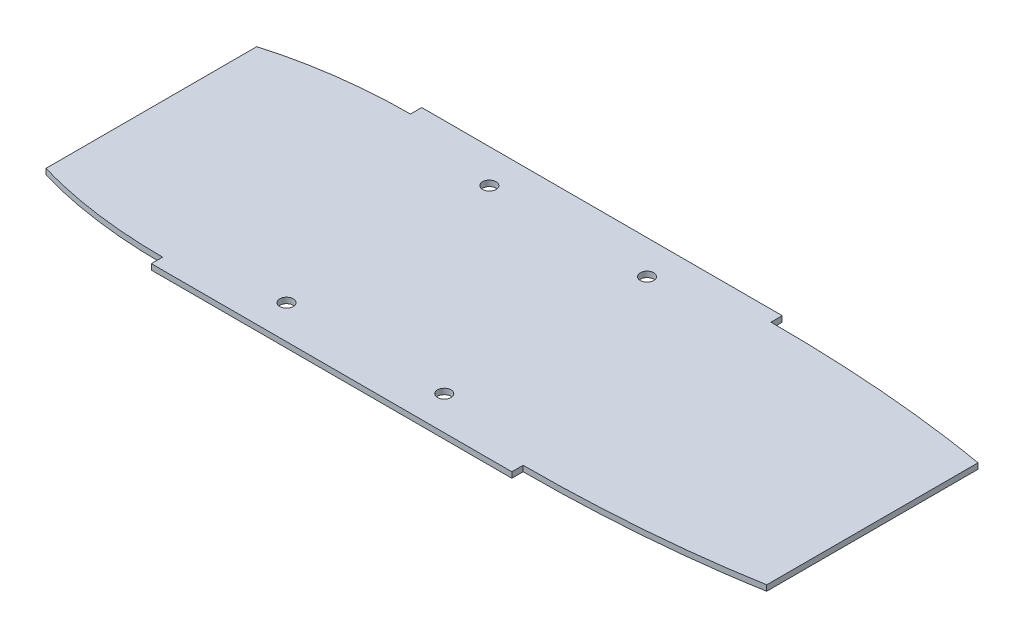
SolidWorks part; units mm, degrees
ref_plane "Front Plane" through (0, 0, 0) normal (0, 0, 1) x (1, 0, 0)
ref_plane "Top Plane" through (0, 0, 0) normal (0, 1, 0) x (1, 0, 0)
ref_plane "Right Plane" through (0, 0, 0) normal (1, 0, 0) x (0, 0, -1)
sketch "Sketch1" plane through (0, 0, 0) normal (0, 1, 0) x (1, 0, 0)
  line L1 (76.2, 38.1) -> (177.8, 38.1)
  line L3 (76.2, -38.1) -> (177.8, -38.1)
  ellipse E0 centre (76.2, 0) end of major axis (0, 0) minor radius 38.1 (76.2, 38.1) -> (76.2, -38.1) ccw
  ellipse E1 centre (177.8, 0) end of major axis (304.8, 0) minor radius 38.1 (177.8, -38.1) -> (177.8, 38.1) ccw
  point P0 (0, 0)
  dimension "D1" = 101.6
  dimension "D2" = 76.2
  dimension "D3" = 127
  dimension "D4" = 76.2
extrude "Boss-Extrude1" add sketch "Sketch1" along normal blind 25.4
sketch "Sketch2" plane through (0, 0, 0) normal (1, 0, 0) x (0, 0, -1)
  line L2 (-38.1, 25.4) -> (-38.1, 0) construction
  line L3 (-38.1, 0) -> (38.1, 0) construction
  circle A0 centre (0, 93.3971) radius 57.15
  point P5 (-38.1, 50.8)
  dimension "D1" = 114.3
  dimension "D2" = 50.8
extrude "Cut-Extrude2" [suppressed] cut sketch "Sketch2" along normal through all
sketch "Sketch3" plane through (0, 0, 0) normal (0, -1, 0) x (1, 0, 0)
  line L1 (152.4, -61.0376) -> (-25.885, -61.0376)
  line L2 (152.4, -61.0376) -> (152.4, 51.2506)
  line L3 (152.4, 51.2506) -> (-25.885, 51.2506)
  line L4 (-25.885, -61.0376) -> (-25.885, 51.2506)
  line L5 (152.4, -61.0376) -> (-25.885, 51.2506) construction
  line L6 (152.4, 51.2506) -> (-25.885, -61.0376) construction
  point P0 (63.2575, -4.8935)
  dimension "D1" = 152.4
extrude "Cut-Extrude3" [suppressed] cut sketch "Sketch3" against normal through all
sketch "Sketch4" plane through (0, 0, 0) normal (0, -1, 0) x (1, 0, 0)
  line L0 (177.8, -38.1) -> (76.2, -38.1) construction
  line L1 (139.7, -38.1) -> (76.2, -38.1)
  line L2 (139.7, -38.1) -> (139.7, 38.1)
  line L3 (139.7, 38.1) -> (76.2, 38.1)
  line L4 (76.2, -38.1) -> (76.2, 38.1)
  line L5 (139.7, -38.1) -> (76.2, 38.1) construction
  line L6 (139.7, 38.1) -> (76.2, -38.1) construction
  point P0 (107.95, 0)
  dimension "D1" = 63.5
extrude "Cut-Extrude4" cut sketch "Sketch4" against normal blind 0.01
hole_wizard "#6 Clearance Hole1" positions "Sketch5" profile "Sketch6" hole size "#6" standard "ANSI Inch" end condition through all
sketch "Sketch5" plane through (0, 25.4, 0) normal (0, 1, 0) x (1, 0, 0)
  line L0 (104.775, 28.575) -> (104.775, -28.575) construction
  line L3 (76.2, -38.1) -> (177.8, -38.1) construction
  point P0 (104.775, 28.575)
  point P2 (149.225, 28.575)
  point P4 (149.225, -28.575)
  point P6 (104.775, -28.575)
  dimension "D1" = 44.45
  dimension "D2" = 57.15
  dimension "D3" = 28.575
  dimension "D4" = 9.525
sketch "Sketch6" plane through (104.775, 25.4, -28.575) normal (1, 0, 0) x (0, 0, 1)
  line L0 (0, 0) -> (0, 25.4)
  line L1 (0, 25.4) -> (1.8986, 25.4)
  line L2 (1.8986, 25.4) -> (1.8986, 0)
  line L5 (1.8986, 0) -> (0, 0)
  line L11 (0, -6.35) -> (0, 107.95) construction
  dimension "Thru Hole Dia." = 3.7973
  dimension "Thru Hole Depth" = 25.4
sketch "Sketch7" plane through (0, 25.4, 0) normal (0, 1, 0) x (1, 0, 0)
  line L1 (144.0924, 28.575) -> (146.6587, 24.13)
  line L2 (146.6587, 24.13) -> (151.7913, 24.13)
  line L3 (151.7913, 24.13) -> (154.3576, 28.575)
  line L4 (154.3576, 28.575) -> (151.7913, 33.02)
  line L5 (151.7913, 33.02) -> (146.6587, 33.02)
  line L6 (146.6587, 33.02) -> (144.0924, 28.575)
  line L7 (144.0924, -28.575) -> (146.6587, -33.02)
  line L8 (146.6587, -33.02) -> (151.7913, -33.02)
  line L9 (151.7913, -33.02) -> (154.3576, -28.575)
  line L10 (154.3576, -28.575) -> (151.7913, -24.13)
  line L11 (151.7913, -24.13) -> (146.6587, -24.13)
  line L12 (146.6587, -24.13) -> (144.0924, -28.575)
  line L13 (99.6424, -28.575) -> (102.2087, -33.02)
  line L14 (102.2087, -33.02) -> (107.3413, -33.02)
  line L15 (107.3413, -33.02) -> (109.9076, -28.575)
  line L16 (109.9076, -28.575) -> (107.3413, -24.13)
  line L17 (107.3413, -24.13) -> (102.2087, -24.13)
  line L18 (102.2087, -24.13) -> (99.6424, -28.575)
  line L19 (99.6424, 28.575) -> (102.2087, 24.13)
  line L20 (102.2087, 24.13) -> (107.3413, 24.13)
  line L21 (107.3413, 24.13) -> (109.9076, 28.575)
  line L22 (109.9076, 28.575) -> (107.3413, 33.02)
  line L23 (107.3413, 33.02) -> (102.2087, 33.02)
  line L24 (102.2087, 33.02) -> (99.6424, 28.575)
  circle A0 centre (149.225, 28.575) radius 4.445 construction
  circle A1 centre (149.225, -28.575) radius 4.445 construction
  circle A2 centre (104.775, -28.575) radius 4.445 construction
  circle A3 centre (104.775, 28.575) radius 4.445 construction
  dimension "D1" = 8.89
  dimension "D2" = 8.89
  dimension "D3" = 8.89
  dimension "D4" = 8.89
extrude "Cut-Extrude5" cut sketch "Sketch7" against normal blind 3.5052
sketch "Sketch8" plane through (0, 25.4, 0) normal (0, 1, 0) x (1, 0, 0)
  line L4 (177.8, 34.925) -> (76.2, 34.925)
  line L5 (76.2, -34.925) -> (177.8, -34.925)
  line L54 (76.2, 34.925) -> (76.2, 38.1)
  line L56 (177.8, 38.1) -> (76.2, 38.1) construction
  line L57 (177.8, 38.1) -> (177.8, 34.925)
  line L58 (76.2, -34.925) -> (76.2, -38.1)
  line L59 (76.2, -38.1) -> (177.8, -38.1)
  line L60 (177.8, -38.1) -> (177.8, -34.925)
  line L61 (76.2, 38.1) -> (177.8, 38.1)
  circle A0 centre (149.225, 28.575) radius 1.8987 construction
  circle A1 centre (149.225, -28.575) radius 1.8987 construction
  circle A2 centre (104.775, -28.575) radius 1.8986 construction
  circle A3 centre (104.775, 28.575) radius 1.8986 construction
  circle A4 centre (149.225, 28.575) radius 1.8987
  circle A5 centre (149.225, -28.575) radius 1.8987
  circle A6 centre (104.775, -28.575) radius 1.8986
  circle A7 centre (104.775, 28.575) radius 1.8986
  ellipse E2 centre (177.8, 0) end of major axis (50.8, 0) minor radius 38.1 (177.8, -38.1) -> (177.8, 38.1) ccw construction
  spline S0 degree 3 poles (-1377.8045, 1206.3591) (-854.0921, 797.9266) (-294.8884, -54.3183) (200.1699, -34.3631) (205.7465, -34.0245) (216.8803, -33.103) (222.4374, -32.5204) (230.7563, -31.4365) (233.5264, -31.04) (239.0605, -30.1693) (241.8261, -29.6947) (250.0889, -28.1436) (255.5586, -26.9423) (262.3286, -25.1517) (263.6791, -24.7789) (266.3727, -24.0005) (267.7168, -23.5946) (271.7259, -22.3246) (274.3674, -21.4094) (279.5692, -19.3996) (282.1298, -18.3061) (285.883, -16.4724) (287.1192, -15.8286) (289.5537, -14.4572) (290.7521, -13.7299) (293.0968, -12.1607) (294.2462, -11.3161) (295.8747, -9.9512) (296.4028, -9.4789) (297.4219, -8.4911) (297.9134, -7.9747) (298.8341, -6.9028) (299.2652, -6.3459) (300.0511, -5.1769) (300.4066, -4.5643) (301.0089, -3.2659) (301.247, -2.5978) (301.485, -1.5601) (301.5446, -1.2061) (301.6178, -0.4946) (301.6449, 0.2142) (301.5814, 0.9176) (301.4741, 1.6184) (301.3978, 1.9698) (301.1113, 3.0015) (300.8464, 3.657) (300.2067, 4.9201) (299.8287, 5.531) (299.0071, 6.6864) (298.5626, 7.2341) (297.6228, 8.2846) (297.1274, 8.7872) (296.0961, 9.7565) (295.5585, 10.2242) (293.9164, 11.5662) (292.7775, 12.3858) (290.4399, 13.9238) (289.2408, 14.6414) (286.7973, 15.9997) (285.5527, 16.6401) (283.0272, 17.8594) (281.7447, 18.4387) (279.1562, 19.5434) (277.8549, 20.0667) (273.9338, 21.5646) (271.2968, 22.4679) (265.9889, 24.1333) (263.3179, 24.8949) (255.2638, 27.0095) (249.8403, 28.1946) (238.9146, 30.2368) (233.4119, 31.0923) (225.1088, 32.1714) (222.3337, 32.4966) (216.7836, 33.0815) (214.0067, 33.3415) (205.6704, 34.0295) (200.1056, 34.3664) (-342.7454, 56.1817) (-942.1991, -973.5849) (-1486.6218, -1072.784) knots -5.414346 -5.414346 -5.414346 -5.414346 0.0625 0.0625 0.125 0.125 0.1875 0.1875 0.21875 0.21875 0.25 0.25 0.3125 0.3125 0.328125 0.328125 0.34375 0.34375 0.375 0.375 0.40625 0.40625 0.421875 0.421875 0.4375 0.4375 0.453125 0.453125 0.460937 0.460937 0.46875 0.46875 0.476562 0.476562 0.484375 0.484375 0.492187 0.492187 0.496094 0.496094 0.5 0.503906 0.503906 0.507812 0.507812 0.515625 0.515625 0.523437 0.523437 0.53125 0.53125 0.539062 0.539062 0.546875 0.546875 0.5625 0.5625 0.578125 0.578125 0.59375 0.59375 0.609375 0.609375 0.625 0.625 0.65625 0.65625 0.6875 0.6875 0.75 0.75 0.8125 0.8125 0.84375 0.84375 0.875 0.875 0.9375 0.9375 6.964681 6.964681 6.964681 6.964681 only from (177.8, -34.925) to (177.8, 34.925)
  spline S1 degree 3 poles (1055.6343, -1687.5294) (614.9818, -466.9883) (294.4055, 51.3664) (61.7544, 34.2641) (58.1825, 33.8682) (51.0865, 32.7961) (47.5624, 32.1204) (40.5691, 30.4484) (37.0996, 29.4531) (32.806, 27.9564) (31.9495, 27.6442) (30.2412, 26.9922) (29.3909, 26.6528) (26.8661, 25.5974) (25.2124, 24.8424) (21.9728, 23.2134) (20.3869, 22.3396) (17.2974, 20.4484) (15.7935, 19.4313) (13.6173, 17.7663) (12.9047, 17.1874) (11.5136, 15.9765) (10.8409, 15.3496) (9.5478, 14.0466) (8.9274, 13.3705) (8.0429, 12.3133) (7.7557, 11.9536) (7.1984, 11.2184) (6.9284, 10.8431) (5.638, 8.9421) (4.781, 7.3318) (4.0115, 5.1647) (3.8724, 4.7214) (3.631, 3.8285) (3.5287, 3.3798) (3.2787, 2.0267) (3.1875, 1.1156) (3.1705, -0.2656) (3.1851, -0.7307) (3.2544, -1.6536) (3.3089, -2.1107) (3.5286, -3.4697) (3.7502, -4.3591) (4.1852, -5.6706) (4.348, -6.1057) (4.7028, -6.9593) (4.8943, -7.3775) (5.5073, -8.6089) (5.9671, -9.3989) (6.9725, -10.9267) (7.5182, -11.6645) (8.6847, -13.0948) (9.2998, -13.7802) (11.2121, -15.7483) (12.5811, -16.951) (14.7395, -18.6328) (15.4767, -19.1727) (16.9829, -20.2157) (17.7538, -20.7198) (20.0907, -22.1703) (21.6832, -23.0577) (26.5435, -25.5293) (29.8928, -26.9256) (35.0379, -28.7409) (36.7735, -29.2986) (39.405, -30.0707) (40.2865, -30.3172) (42.0504, -30.7874) (42.9338, -31.0114) (47.3578, -32.0793) (50.919, -32.7671) (58.0795, -33.8562) (61.6788, -34.2572) (316.9315, -53.1148) (654.4248, 576.1538) (1055.7992, 1687.4516) knots -3.920308 -3.920308 -3.920308 -3.920308 0.0625 0.0625 0.125 0.125 0.1875 0.1875 0.25 0.25 0.265625 0.265625 0.28125 0.28125 0.3125 0.3125 0.34375 0.34375 0.375 0.375 0.390625 0.390625 0.40625 0.40625 0.421875 0.421875 0.429688 0.429688 0.4375 0.4375 0.46875 0.46875 0.476563 0.476563 0.484375 0.484375 0.5 0.5 0.507813 0.507813 0.515625 0.515625 0.53125 0.53125 0.539063 0.539063 0.546875 0.546875 0.5625 0.5625 0.578125 0.578125 0.59375 0.59375 0.625 0.625 0.640625 0.640625 0.65625 0.65625 0.6875 0.6875 0.75 0.75 0.78125 0.78125 0.796875 0.796875 0.8125 0.8125 0.875 0.875 0.9375 0.9375 5.285634 5.285634 5.285634 5.285634 only from (76.2, 34.925) to (76.2, -34.925)
  spline S2 degree 3 poles (177.8, -34.925) (183.4037, -34.925) (188.9985, -34.8134) (200.1699, -34.3631) (205.7465, -34.0245) (216.8803, -33.103) (222.4374, -32.5204) (230.7563, -31.4365) (233.5264, -31.04) (239.0605, -30.1693) (241.8261, -29.6947) (250.0889, -28.1436) (255.5586, -26.9423) (262.3286, -25.1517) (263.6791, -24.7789) (266.3727, -24.0005) (267.7168, -23.5946) (271.7259, -22.3246) (274.3674, -21.4094) (279.5692, -19.3996) (282.1298, -18.3061) (285.883, -16.4724) (287.1192, -15.8286) (289.5537, -14.4572) (290.7521, -13.7299) (293.0968, -12.1607) (294.2462, -11.3161) (295.8747, -9.9512) (296.4028, -9.4789) (297.4219, -8.4911) (297.9134, -7.9747) (298.8341, -6.9028) (299.2652, -6.3459) (300.0511, -5.1769) (300.4066, -4.5643) (301.0089, -3.2659) (301.247, -2.5978) (301.485, -1.5601) (301.5446, -1.2061) (301.6178, -0.4946) (301.6449, 0.2142) (301.5814, 0.9176) (301.4741, 1.6184) (301.3978, 1.9698) (301.1113, 3.0015) (300.8464, 3.657) (300.2067, 4.9201) (299.8287, 5.531) (299.0071, 6.6864) (298.5626, 7.2341) (297.6228, 8.2846) (297.1274, 8.7872) (296.0961, 9.7565) (295.5585, 10.2242) (293.9164, 11.5662) (292.7775, 12.3858) (290.4399, 13.9238) (289.2408, 14.6414) (286.7973, 15.9997) (285.5527, 16.6401) (283.0272, 17.8594) (281.7447, 18.4387) (279.1562, 19.5434) (277.8549, 20.0667) (273.9338, 21.5646) (271.2968, 22.4679) (265.9889, 24.1333) (263.3179, 24.8949) (255.2638, 27.0095) (249.8403, 28.1946) (238.9146, 30.2368) (233.4119, 31.0923) (225.1088, 32.1714) (222.3337, 32.4966) (216.7836, 33.0815) (214.0067, 33.3415) (205.6704, 34.0295) (200.1056, 34.3664) (188.9628, 34.8142) (183.3847, 34.925) (177.8, 34.925) knots 0 0 0 0 0.0625 0.0625 0.125 0.125 0.1875 0.1875 0.21875 0.21875 0.25 0.25 0.3125 0.3125 0.328125 0.328125 0.34375 0.34375 0.375 0.375 0.40625 0.40625 0.421875 0.421875 0.4375 0.4375 0.453125 0.453125 0.460937 0.460937 0.46875 0.46875 0.476562 0.476562 0.484375 0.484375 0.492187 0.492187 0.496094 0.496094 0.5 0.503906 0.503906 0.507812 0.507812 0.515625 0.515625 0.523437 0.523437 0.53125 0.53125 0.539062 0.539062 0.546875 0.546875 0.5625 0.5625 0.578125 0.578125 0.59375 0.59375 0.609375 0.609375 0.625 0.625 0.65625 0.65625 0.6875 0.6875 0.75 0.75 0.8125 0.8125 0.84375 0.84375 0.875 0.875 0.9375 0.9375 1 1 1 1
  spline S3 degree 3 poles (76.2, 34.925) (72.5604, 34.925) (68.9434, 34.7926) (61.7544, 34.2641) (58.1825, 33.8682) (51.0865, 32.7961) (47.5624, 32.1204) (40.5691, 30.4484) (37.0996, 29.4531) (32.806, 27.9564) (31.9495, 27.6442) (30.2412, 26.9922) (29.3909, 26.6528) (26.8661, 25.5974) (25.2124, 24.8424) (21.9728, 23.2134) (20.3869, 22.3396) (17.2974, 20.4484) (15.7935, 19.4313) (13.6173, 17.7663) (12.9047, 17.1874) (11.5136, 15.9765) (10.8409, 15.3496) (9.5478, 14.0466) (8.9274, 13.3705) (8.0429, 12.3133) (7.7557, 11.9536) (7.1984, 11.2184) (6.9284, 10.8431) (5.638, 8.9421) (4.781, 7.3318) (4.0115, 5.1647) (3.8724, 4.7214) (3.631, 3.8285) (3.5287, 3.3798) (3.2787, 2.0267) (3.1875, 1.1156) (3.1705, -0.2656) (3.1851, -0.7307) (3.2544, -1.6536) (3.3089, -2.1107) (3.5286, -3.4697) (3.7502, -4.3591) (4.1852, -5.6706) (4.348, -6.1057) (4.7028, -6.9593) (4.8943, -7.3775) (5.5073, -8.6089) (5.9671, -9.3989) (6.9725, -10.9267) (7.5182, -11.6645) (8.6847, -13.0948) (9.2998, -13.7802) (11.2121, -15.7483) (12.5811, -16.951) (14.7395, -18.6328) (15.4767, -19.1727) (16.9829, -20.2157) (17.7538, -20.7198) (20.0907, -22.1703) (21.6832, -23.0577) (26.5435, -25.5293) (29.8928, -26.9256) (35.0379, -28.7409) (36.7735, -29.2986) (39.405, -30.0707) (40.2865, -30.3172) (42.0504, -30.7874) (42.9338, -31.0114) (47.3578, -32.0793) (50.919, -32.7671) (58.0795, -33.8562) (61.6788, -34.2572) (68.9128, -34.7916) (72.5476, -34.925) (76.2, -34.925) knots 0 0 0 0 0.0625 0.0625 0.125 0.125 0.1875 0.1875 0.25 0.25 0.265625 0.265625 0.28125 0.28125 0.3125 0.3125 0.34375 0.34375 0.375 0.375 0.390625 0.390625 0.40625 0.40625 0.421875 0.421875 0.429688 0.429688 0.4375 0.4375 0.46875 0.46875 0.476563 0.476563 0.484375 0.484375 0.5 0.5 0.507813 0.507813 0.515625 0.515625 0.53125 0.53125 0.539063 0.539063 0.546875 0.546875 0.5625 0.5625 0.578125 0.578125 0.59375 0.59375 0.625 0.625 0.640625 0.640625 0.65625 0.65625 0.6875 0.6875 0.75 0.75 0.78125 0.78125 0.796875 0.796875 0.8125 0.8125 0.875 0.875 0.9375 0.9375 1 1 1 1
  dimension "D1" = 3.175
extrude "Boss-Extrude2" add sketch "Sketch8" along normal blind 1.5875
sketch "Sketch9" plane through (0, 0, 0) normal (1, 0, 0) x (0, 0, -1)
  line L0 (34.925, 25.4) -> (38.1, 25.4) construction
  line L1 (-41.2871, 25.4) -> (42.2254, 25.4)
  line L2 (-41.2871, 25.4) -> (-41.2871, -1.2646)
  line L3 (-41.2871, -1.2646) -> (42.2254, -1.2646)
  line L4 (42.2254, 25.4) -> (42.2254, -1.2646)
extrude "Cut-Extrude7" cut sketch "Sketch9" along normal through all
sketch "Sketch10" plane through (0, 25.4, 0) normal (0, -1, 0) x (1, 0, 0)
  line L0 (76.2, 34.925) -> (76.2, 38.1) construction
  line L1 (-38.1, 39.0175) -> (38.1, 39.0175)
  line L2 (-38.1, 39.0175) -> (-38.1, -39.0175)
  line L3 (-38.1, -39.0175) -> (38.1, -39.0175)
  line L4 (38.1, 39.0175) -> (38.1, -39.0175)
  line L5 (-38.1, 39.0175) -> (38.1, -39.0175) construction
  line L6 (-38.1, -39.0175) -> (38.1, 39.0175) construction
  line L7 (177.8, 38.1) -> (177.8, 34.925) construction
  line L8 (361.95, 44.8802) -> (241.3, 44.8802)
  line L9 (361.95, 44.8802) -> (361.95, -44.8805)
  line L10 (361.95, -44.8805) -> (241.3, -44.8805)
  line L11 (241.3, 44.8802) -> (241.3, -44.8805)
  line L12 (361.95, 44.8802) -> (241.3, -44.8805) construction
  line L13 (361.95, -44.8805) -> (241.3, 44.8802) construction
  spline S0 degree 3 poles (177.8, 34.925) (183.4037, 34.925) (188.9985, 34.8134) (200.1699, 34.3631) (205.7465, 34.0245) (216.8803, 33.103) (222.4374, 32.5204) (230.7563, 31.4365) (233.5264, 31.04) (239.0605, 30.1693) (241.8261, 29.6947) (250.0889, 28.1436) (255.5586, 26.9423) (262.3286, 25.1517) (263.6791, 24.7789) (266.3727, 24.0005) (267.7168, 23.5946) (271.7259, 22.3246) (274.3674, 21.4094) (279.5692, 19.3996) (282.1298, 18.3061) (285.883, 16.4724) (287.1192, 15.8286) (289.5537, 14.4572) (290.7521, 13.7299) (293.0968, 12.1607) (294.2462, 11.3161) (295.8747, 9.9512) (296.4028, 9.4789) (297.4219, 8.4911) (297.9134, 7.9747) (298.8341, 6.9028) (299.2652, 6.3459) (300.0511, 5.1769) (300.4066, 4.5643) (301.0089, 3.2659) (301.247, 2.5978) (301.485, 1.5601) (301.5446, 1.2061) (301.6178, 0.4946) (301.6449, -0.2142) (301.5814, -0.9176) (301.4741, -1.6184) (301.3978, -1.9698) (301.1113, -3.0015) (300.8464, -3.657) (300.2067, -4.9201) (299.8287, -5.531) (299.0071, -6.6864) (298.5626, -7.2341) (297.6228, -8.2846) (297.1274, -8.7872) (296.0961, -9.7565) (295.5585, -10.2242) (293.9164, -11.5662) (292.7775, -12.3858) (290.4399, -13.9238) (289.2408, -14.6414) (286.7973, -15.9997) (285.5527, -16.6401) (283.0272, -17.8594) (281.7447, -18.4387) (279.1562, -19.5434) (277.8549, -20.0667) (273.9338, -21.5646) (271.2968, -22.4679) (265.9889, -24.1333) (263.3179, -24.8949) (255.2638, -27.0095) (249.8403, -28.1946) (238.9146, -30.2368) (233.4119, -31.0923) (225.1088, -32.1714) (222.3337, -32.4966) (216.7836, -33.0815) (214.0067, -33.3415) (205.6704, -34.0295) (200.1056, -34.3664) (188.9628, -34.8142) (183.3847, -34.925) (177.8, -34.925) knots 0 0 0 0 0.0625 0.0625 0.125 0.125 0.1875 0.1875 0.21875 0.21875 0.25 0.25 0.3125 0.3125 0.328125 0.328125 0.34375 0.34375 0.375 0.375 0.40625 0.40625 0.421875 0.421875 0.4375 0.4375 0.453125 0.453125 0.460937 0.460937 0.46875 0.46875 0.476562 0.476562 0.484375 0.484375 0.492187 0.492187 0.496094 0.496094 0.5 0.503906 0.503906 0.507812 0.507812 0.515625 0.515625 0.523437 0.523437 0.53125 0.53125 0.539062 0.539062 0.546875 0.546875 0.5625 0.5625 0.578125 0.578125 0.59375 0.59375 0.609375 0.609375 0.625 0.625 0.65625 0.65625 0.6875 0.6875 0.75 0.75 0.8125 0.8125 0.84375 0.84375 0.875 0.875 0.9375 0.9375 1 1 1 1 construction
  point P0 (0, 0)
  point P8 (76.2, 36.5125)
  point P9 (301.625, -0.0001)
  dimension "D1" = 38.1
  dimension "D2" = 63.5
extrude "Cut-Extrude8" cut sketch "Sketch10" against normal through all
